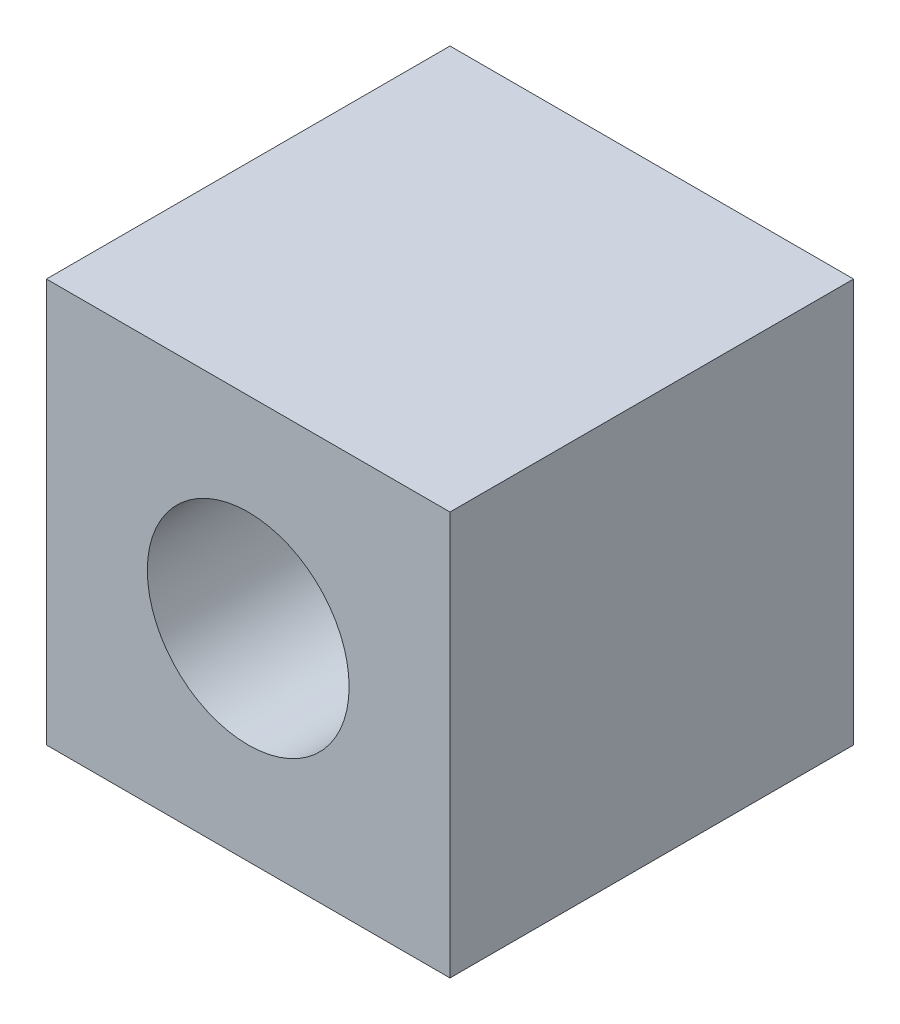
SolidWorks part; units mm, degrees
ref_plane "Front Plane" through (0, 0, 0) normal (0, 0, 1) x (1, 0, 0)
ref_plane "Top Plane" through (0, 0, 0) normal (0, 1, 0) x (1, 0, 0)
ref_plane "Right Plane" through (0, 0, 0) normal (1, 0, 0) x (0, 0, -1)
sketch "Sketch1" plane through (0, 0, 0) normal (0, 0, 1) x (1, 0, 0)
  line L1 (0, 0) -> (10, 0)
  line L2 (0, 0) -> (0, 10)
  line L3 (0, 10) -> (10, 10)
  line L4 (10, 0) -> (10, 10)
extrude "Boss-Extrude1" add sketch "Sketch1" along normal blind 10
sketch "Sketch2" plane through (0, 0, 10) normal (0, 0, 1) x (1, 0, 0)
  circle A0 centre (5, 5) radius 2.5
extrude "Cut-Extrude1" cut sketch "Sketch2" against normal through all
